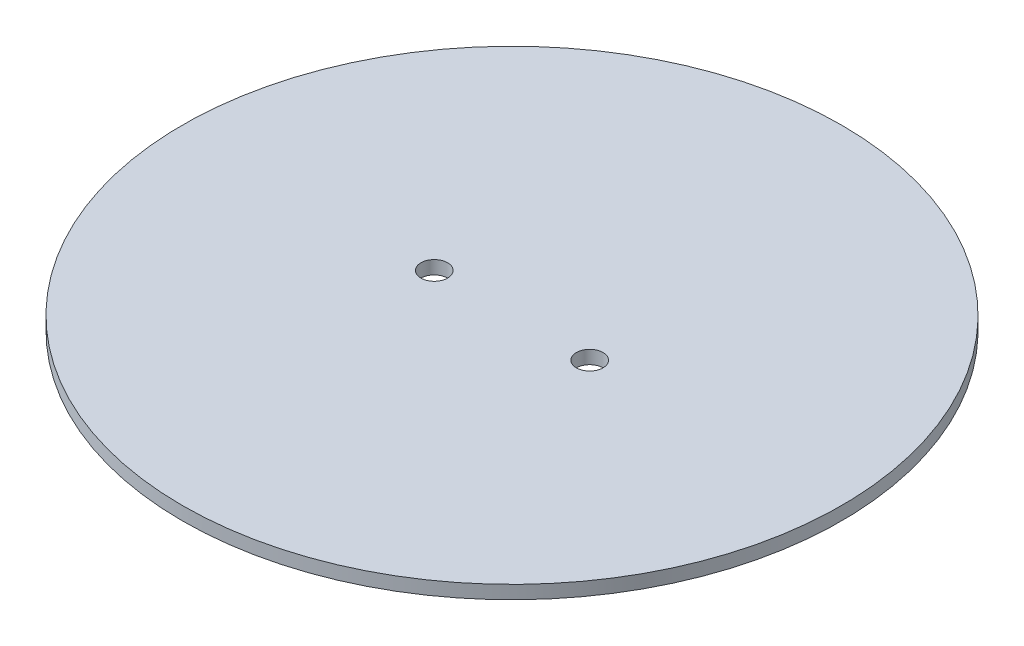
SolidWorks part; units mm, degrees
ref_plane "Front Plane" through (0, 0, 0) normal (0, 0, 1) x (1, 0, 0)
ref_plane "Top Plane" through (0, 0, 0) normal (0, 1, 0) x (1, 0, 0)
ref_plane "Right Plane" through (0, 0, 0) normal (1, 0, 0) x (0, 0, -1)
sketch "Sketch1" plane through (0, 0, 0) normal (0, 1, 0) x (1, 0, 0)
  circle A0 centre (0, 0) radius 74.2
  circle A1 centre (-17.5, 0) radius 3
  circle A2 centre (17.5, 0) radius 3
  dimension "D1" = 148.4
  dimension "D2" = 6
  dimension "D3" = 6
  dimension "D4" = 17.5
  dimension "D5" = 17.5
extrude "Boss-Extrude1" add sketch "Sketch1" along normal blind 3
